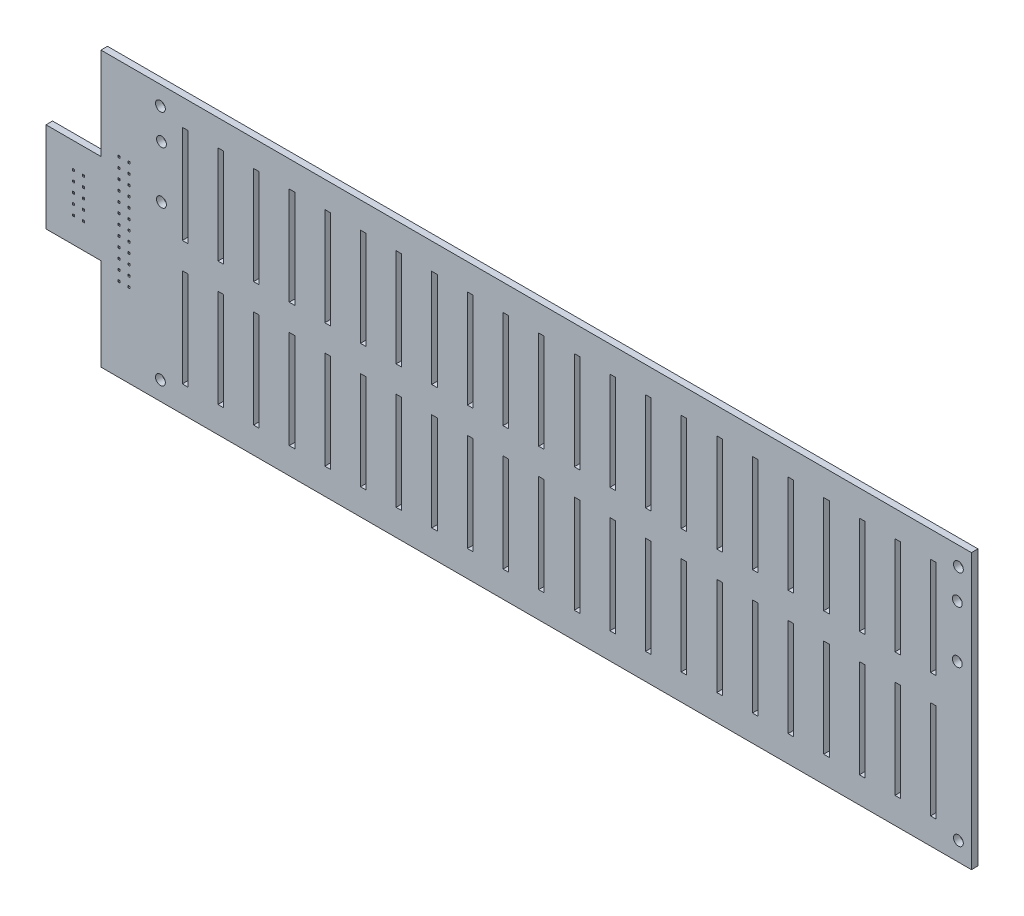
SolidWorks part; units mm, degrees
ref_plane "Front Plane" through (0, 0, 0) normal (0, 0, 1) x (1, 0, 0)
ref_plane "Top Plane" through (0, 0, 0) normal (0, 1, 0) x (1, 0, 0)
ref_plane "Right Plane" through (0, 0, 0) normal (1, 0, 0) x (0, 0, -1)
sketch "Model" plane through (0, 0, 0) normal (0, 0, 1) x (1, 0, 0)
  line L0 (-140.24, -42) -> (126.05, -42)
  line L1 (126.05, -42) -> (126.05, 42)
  line L2 (126.05, 42) -> (-140.24, 42)
  line L3 (-140.24, 42) -> (-140.24, 13.8)
  line L4 (-140.24, 13.8) -> (-157.05, 13.8)
  line L5 (-157.05, 13.8) -> (-157.05, -13.8)
  line L6 (-157.05, -13.8) -> (-140.24, -13.8)
  line L7 (-140.24, -13.8) -> (-140.24, -42)
  line L8 (-131.39, -1.18) -> (-132.03, -1.18)
  line L9 (-131.39, -1.82) -> (-131.39, -1.18)
  line L10 (-132.03, -1.82) -> (-131.39, -1.82)
  line L11 (-132.03, -1.18) -> (-132.03, -1.82)
  line L12 (-134.39, 1.82) -> (-135.03, 1.82)
  line L13 (-134.39, 1.18) -> (-134.39, 1.82)
  line L14 (-135.03, 1.18) -> (-134.39, 1.18)
  line L15 (-135.03, 1.82) -> (-135.03, 1.18)
  line L16 (-131.39, 1.82) -> (-132.03, 1.82)
  line L17 (-131.39, 1.18) -> (-131.39, 1.82)
  line L18 (-132.03, 1.18) -> (-131.39, 1.18)
  line L19 (-132.03, 1.82) -> (-132.03, 1.18)
  line L20 (-134.39, 4.82) -> (-135.03, 4.82)
  line L21 (-134.39, 4.18) -> (-134.39, 4.82)
  line L22 (-135.03, 4.18) -> (-134.39, 4.18)
  line L23 (-135.03, 4.82) -> (-135.03, 4.18)
  line L24 (-131.39, -7.18) -> (-132.03, -7.18)
  line L25 (-131.39, -7.82) -> (-131.39, -7.18)
  line L26 (-132.03, -7.82) -> (-131.39, -7.82)
  line L27 (-132.03, -7.18) -> (-132.03, -7.82)
  line L28 (-134.39, -4.18) -> (-135.03, -4.18)
  line L29 (-134.39, -4.82) -> (-134.39, -4.18)
  line L30 (-135.03, -4.82) -> (-134.39, -4.82)
  line L31 (-135.03, -4.18) -> (-135.03, -4.82)
  line L32 (-131.39, -4.18) -> (-132.03, -4.18)
  line L33 (-131.39, -4.82) -> (-131.39, -4.18)
  line L34 (-132.03, -4.82) -> (-131.39, -4.82)
  line L35 (-132.03, -4.18) -> (-132.03, -4.82)
  line L36 (-134.39, -1.18) -> (-135.03, -1.18)
  line L37 (-134.39, -1.82) -> (-134.39, -1.18)
  line L38 (-135.03, -1.82) -> (-134.39, -1.82)
  line L39 (-135.03, -1.18) -> (-135.03, -1.82)
  line L40 (-134.39, 10.82) -> (-135.03, 10.82)
  line L41 (-134.39, 10.18) -> (-134.39, 10.82)
  line L42 (-135.03, 10.18) -> (-134.39, 10.18)
  line L43 (-135.03, 10.82) -> (-135.03, 10.18)
  line L44 (-134.39, 13.82) -> (-135.03, 13.82)
  line L45 (-134.39, 13.18) -> (-134.39, 13.82)
  line L46 (-135.03, 13.18) -> (-134.39, 13.18)
  line L47 (-135.03, 13.82) -> (-135.03, 13.18)
  line L48 (-131.39, 13.82) -> (-132.03, 13.82)
  line L49 (-131.39, 13.18) -> (-131.39, 13.82)
  line L50 (-132.03, 13.18) -> (-131.39, 13.18)
  line L51 (-132.03, 13.82) -> (-132.03, 13.18)
  line L52 (-134.39, 16.82) -> (-135.03, 16.82)
  line L53 (-134.39, 16.18) -> (-134.39, 16.82)
  line L54 (-135.03, 16.18) -> (-134.39, 16.18)
  line L55 (-135.03, 16.82) -> (-135.03, 16.18)
  line L56 (-131.39, 4.82) -> (-132.03, 4.82)
  line L57 (-131.39, 4.18) -> (-131.39, 4.82)
  line L58 (-132.03, 4.18) -> (-131.39, 4.18)
  line L59 (-132.03, 4.82) -> (-132.03, 4.18)
  line L60 (-134.39, 7.82) -> (-135.03, 7.82)
  line L61 (-134.39, 7.18) -> (-134.39, 7.82)
  line L62 (-135.03, 7.18) -> (-134.39, 7.18)
  line L63 (-135.03, 7.82) -> (-135.03, 7.18)
  line L64 (-131.39, 7.82) -> (-132.03, 7.82)
  line L65 (-131.39, 7.18) -> (-131.39, 7.82)
  line L66 (-132.03, 7.18) -> (-131.39, 7.18)
  line L67 (-132.03, 7.82) -> (-132.03, 7.18)
  line L68 (-131.39, 10.82) -> (-132.03, 10.82)
  line L69 (-131.39, 10.18) -> (-131.39, 10.82)
  line L70 (-132.03, 10.18) -> (-131.39, 10.18)
  line L71 (-132.03, 10.82) -> (-132.03, 10.18)
  line L72 (-145.9, -0.32) -> (-145.26, -0.32)
  line L73 (-145.9, 0.32) -> (-145.9, -0.32)
  line L74 (-145.26, 0.32) -> (-145.9, 0.32)
  line L75 (-145.26, -0.32) -> (-145.26, 0.32)
  line L76 (-148.9, 2.68) -> (-148.26, 2.68)
  line L77 (-148.9, 3.32) -> (-148.9, 2.68)
  line L78 (-148.26, 3.32) -> (-148.9, 3.32)
  line L79 (-148.26, 2.68) -> (-148.26, 3.32)
  line L80 (-145.9, 2.68) -> (-145.26, 2.68)
  line L81 (-145.9, 3.32) -> (-145.9, 2.68)
  line L82 (-145.26, 3.32) -> (-145.9, 3.32)
  line L83 (-145.26, 2.68) -> (-145.26, 3.32)
  line L84 (-148.9, 5.68) -> (-148.26, 5.68)
  line L85 (-148.9, 6.32) -> (-148.9, 5.68)
  line L86 (-148.26, 6.32) -> (-148.9, 6.32)
  line L87 (-148.26, 5.68) -> (-148.26, 6.32)
  line L88 (-145.9, -6.32) -> (-145.26, -6.32)
  line L89 (-145.9, -5.68) -> (-145.9, -6.32)
  line L90 (-145.26, -5.68) -> (-145.9, -5.68)
  line L91 (-145.26, -6.32) -> (-145.26, -5.68)
  line L92 (-148.9, -3.32) -> (-148.26, -3.32)
  line L93 (-148.9, -2.68) -> (-148.9, -3.32)
  line L94 (-148.26, -2.68) -> (-148.9, -2.68)
  line L95 (-148.26, -3.32) -> (-148.26, -2.68)
  line L96 (-145.9, -3.32) -> (-145.26, -3.32)
  line L97 (-145.9, -2.68) -> (-145.9, -3.32)
  line L98 (-145.26, -2.68) -> (-145.9, -2.68)
  line L99 (-145.26, -3.32) -> (-145.26, -2.68)
  line L100 (-148.9, -0.32) -> (-148.26, -0.32)
  line L101 (-148.9, 0.32) -> (-148.9, -0.32)
  line L102 (-148.26, 0.32) -> (-148.9, 0.32)
  line L103 (-148.26, -0.32) -> (-148.26, 0.32)
  line L104 (-131.39, -13.18) -> (-132.03, -13.18)
  line L105 (-131.39, -13.82) -> (-131.39, -13.18)
  line L106 (-132.03, -13.82) -> (-131.39, -13.82)
  line L107 (-132.03, -13.18) -> (-132.03, -13.82)
  line L108 (-134.39, -10.18) -> (-135.03, -10.18)
  line L109 (-134.39, -10.82) -> (-134.39, -10.18)
  line L110 (-135.03, -10.82) -> (-134.39, -10.82)
  line L111 (-135.03, -10.18) -> (-135.03, -10.82)
  line L112 (-131.39, -10.18) -> (-132.03, -10.18)
  line L113 (-131.39, -10.82) -> (-131.39, -10.18)
  line L114 (-132.03, -10.82) -> (-131.39, -10.82)
  line L115 (-132.03, -10.18) -> (-132.03, -10.82)
  line L116 (-134.39, -7.18) -> (-135.03, -7.18)
  line L117 (-134.39, -7.82) -> (-134.39, -7.18)
  line L118 (-135.03, -7.82) -> (-134.39, -7.82)
  line L119 (-135.03, -7.18) -> (-135.03, -7.82)
  line L120 (-145.9, 5.68) -> (-145.26, 5.68)
  line L121 (-145.9, 6.32) -> (-145.9, 5.68)
  line L122 (-145.26, 6.32) -> (-145.9, 6.32)
  line L123 (-145.26, 5.68) -> (-145.26, 6.32)
  line L124 (-134.39, -16.18) -> (-135.03, -16.18)
  line L125 (-134.39, -16.82) -> (-134.39, -16.18)
  line L126 (-135.03, -16.82) -> (-134.39, -16.82)
  line L127 (-135.03, -16.18) -> (-135.03, -16.82)
  line L128 (-131.39, -16.18) -> (-132.03, -16.18)
  line L129 (-131.39, -16.82) -> (-131.39, -16.18)
  line L130 (-132.03, -16.82) -> (-131.39, -16.82)
  line L131 (-132.03, -16.18) -> (-132.03, -16.82)
  line L132 (-134.39, -13.18) -> (-135.03, -13.18)
  line L133 (-134.39, -13.82) -> (-134.39, -13.18)
  line L134 (-135.03, -13.82) -> (-134.39, -13.82)
  line L135 (-135.03, -13.18) -> (-135.03, -13.82)
  line L136 (-131.39, 16.82) -> (-132.03, 16.82)
  line L137 (-131.39, 16.18) -> (-131.39, 16.82)
  line L138 (-132.03, 16.18) -> (-131.39, 16.18)
  line L139 (-132.03, 16.82) -> (-132.03, 16.18)
  line L140 (-148.9, -6.32) -> (-148.26, -6.32)
  line L141 (-148.9, -5.68) -> (-148.9, -6.32)
  line L142 (-148.26, -5.68) -> (-148.9, -5.68)
  line L143 (-148.26, -6.32) -> (-148.26, -5.68)
  line L144 (-104.45, 34) -> (-104.45, 4)
  line L145 (-102.75, 34) -> (-104.45, 34)
  line L146 (-102.75, 4) -> (-102.75, 34)
  line L147 (-104.45, 4) -> (-102.75, 4)
  line L157 (-93.55, 34) -> (-93.55, 4)
  line L158 (-91.85, 34) -> (-93.55, 34)
  line L159 (-91.85, 4) -> (-91.85, 34)
  line L160 (-93.55, 4) -> (-91.85, 4)
  line L162 (-82.65, 34) -> (-82.65, 4)
  line L163 (-80.95, 34) -> (-82.65, 34)
  line L172 (-80.95, 4) -> (-80.95, 34)
  line L173 (-82.65, 4) -> (-80.95, 4)
  line L175 (-71.75, 34) -> (-71.75, 4)
  line L176 (-70.05, 34) -> (-71.75, 34)
  line L177 (-70.05, 4) -> (-70.05, 34)
  line L178 (-71.75, 4) -> (-70.05, 4)
  line L188 (-60.85, 34) -> (-60.85, 4)
  line L189 (-59.15, 34) -> (-60.85, 34)
  line L190 (-59.15, 4) -> (-59.15, 34)
  line L191 (-60.85, 4) -> (-59.15, 4)
  line L193 (-49.95, 34) -> (-49.95, 4)
  line L194 (-48.25, 34) -> (-49.95, 34)
  line L195 (-48.25, 4) -> (-48.25, 34)
  line L204 (-49.95, 4) -> (-48.25, 4)
  line L206 (-39.05, 34) -> (-39.05, 4)
  line L207 (-37.35, 34) -> (-39.05, 34)
  line L208 (-37.35, 4) -> (-37.35, 34)
  line L209 (-39.05, 4) -> (-37.35, 4)
  line L211 (-28.15, 34) -> (-28.15, 4)
  line L220 (-26.45, 34) -> (-28.15, 34)
  line L221 (-26.45, 4) -> (-26.45, 34)
  line L222 (-28.15, 4) -> (-26.45, 4)
  line L224 (-17.25, 34) -> (-17.25, 4)
  line L225 (-15.55, 34) -> (-17.25, 34)
  line L226 (-15.55, 4) -> (-15.55, 34)
  line L227 (-17.25, 4) -> (-15.55, 4)
  line L236 (-115.35, 34) -> (-115.35, 4)
  line L237 (-113.65, 34) -> (-115.35, 34)
  line L238 (-113.65, 4) -> (-113.65, 34)
  line L239 (-115.35, 4) -> (-113.65, 4)
  line L241 (-6.35, 34) -> (-6.35, 4)
  line L242 (-4.65, 34) -> (-6.35, 34)
  line L243 (-4.65, 4) -> (-4.65, 34)
  line L252 (-6.35, 4) -> (-4.65, 4)
  line L254 (4.55, 34) -> (4.55, 4)
  line L255 (6.25, 34) -> (4.55, 34)
  line L256 (6.25, 4) -> (6.25, 34)
  line L257 (4.55, 4) -> (6.25, 4)
  line L259 (15.45, 34) -> (15.45, 4)
  line L268 (17.15, 34) -> (15.45, 34)
  line L269 (17.15, 4) -> (17.15, 34)
  line L270 (15.45, 4) -> (17.15, 4)
  line L280 (26.35, 34) -> (26.35, 4)
  line L281 (28.05, 34) -> (26.35, 34)
  line L282 (28.05, 4) -> (28.05, 34)
  line L283 (26.35, 4) -> (28.05, 4)
  line L285 (37.25, 34) -> (37.25, 4)
  line L286 (38.95, 34) -> (37.25, 34)
  line L287 (38.95, 4) -> (38.95, 34)
  line L296 (37.25, 4) -> (38.95, 4)
  line L298 (48.15, 34) -> (48.15, 4)
  line L299 (49.85, 34) -> (48.15, 34)
  line L300 (49.85, 4) -> (49.85, 34)
  line L301 (48.15, 4) -> (49.85, 4)
  line L303 (59.05, 34) -> (59.05, 4)
  line L312 (60.75, 34) -> (59.05, 34)
  line L313 (60.75, 4) -> (60.75, 34)
  line L314 (59.05, 4) -> (60.75, 4)
  line L316 (69.95, 34) -> (69.95, 4)
  line L317 (71.65, 34) -> (69.95, 34)
  line L318 (71.65, 4) -> (71.65, 34)
  line L319 (69.95, 4) -> (71.65, 4)
  line L320 (0, 0) -> (0, 42) construction
  line L321 (-115.35, 19) -> (115.35, 19) construction
  line L322 (0, 0) -> (24.0524, 0) construction
  line L324 (80.85, 34) -> (80.85, 4)
  line L325 (82.55, 34) -> (80.85, 34)
  line L326 (82.55, 4) -> (82.55, 34)
  line L327 (80.85, 4) -> (82.55, 4)
  line L329 (91.75, 34) -> (91.75, 4)
  line L330 (93.45, 34) -> (91.75, 34)
  line L331 (93.45, 4) -> (93.45, 34)
  line L332 (91.75, 4) -> (93.45, 4)
  line L334 (102.65, 34) -> (102.65, 4)
  line L335 (104.35, 34) -> (102.65, 34)
  line L336 (104.35, 4) -> (104.35, 34)
  line L337 (102.65, 4) -> (104.35, 4)
  line L339 (113.55, 34) -> (113.55, 4)
  line L340 (115.25, 34) -> (113.55, 34)
  line L341 (115.25, 4) -> (115.25, 34)
  line L342 (113.55, 4) -> (115.25, 4)
  line L345 (-115.35, -19) -> (115.35, -19) construction
  line L346 (113.55, -4) -> (115.25, -4)
  line L347 (115.25, -4) -> (115.25, -34)
  line L348 (115.25, -34) -> (113.55, -34)
  line L349 (113.55, -34) -> (113.55, -4)
  line L350 (102.65, -4) -> (104.35, -4)
  line L351 (104.35, -4) -> (104.35, -34)
  line L352 (104.35, -34) -> (102.65, -34)
  line L353 (102.65, -34) -> (102.65, -4)
  line L354 (91.75, -4) -> (93.45, -4)
  line L355 (93.45, -4) -> (93.45, -34)
  line L356 (93.45, -34) -> (91.75, -34)
  line L357 (91.75, -34) -> (91.75, -4)
  line L358 (80.85, -4) -> (82.55, -4)
  line L359 (82.55, -4) -> (82.55, -34)
  line L360 (82.55, -34) -> (80.85, -34)
  line L361 (80.85, -34) -> (80.85, -4)
  line L362 (69.95, -4) -> (71.65, -4)
  line L363 (71.65, -4) -> (71.65, -34)
  line L364 (71.65, -34) -> (69.95, -34)
  line L365 (69.95, -34) -> (69.95, -4)
  line L366 (59.05, -4) -> (60.75, -4)
  line L367 (60.75, -4) -> (60.75, -34)
  line L368 (60.75, -34) -> (59.05, -34)
  line L369 (59.05, -34) -> (59.05, -4)
  line L370 (48.15, -4) -> (49.85, -4)
  line L371 (49.85, -4) -> (49.85, -34)
  line L372 (49.85, -34) -> (48.15, -34)
  line L373 (48.15, -34) -> (48.15, -4)
  line L374 (37.25, -4) -> (38.95, -4)
  line L375 (38.95, -4) -> (38.95, -34)
  line L376 (38.95, -34) -> (37.25, -34)
  line L377 (37.25, -34) -> (37.25, -4)
  line L378 (26.35, -4) -> (28.05, -4)
  line L379 (28.05, -4) -> (28.05, -34)
  line L380 (28.05, -34) -> (26.35, -34)
  line L381 (26.35, -34) -> (26.35, -4)
  line L382 (15.45, -4) -> (17.15, -4)
  line L383 (17.15, -4) -> (17.15, -34)
  line L384 (17.15, -34) -> (15.45, -34)
  line L385 (15.45, -34) -> (15.45, -4)
  line L386 (4.55, -4) -> (6.25, -4)
  line L387 (6.25, -4) -> (6.25, -34)
  line L388 (6.25, -34) -> (4.55, -34)
  line L389 (4.55, -34) -> (4.55, -4)
  line L390 (-6.35, -4) -> (-4.65, -4)
  line L391 (-4.65, -4) -> (-4.65, -34)
  line L392 (-4.65, -34) -> (-6.35, -34)
  line L393 (-6.35, -34) -> (-6.35, -4)
  line L394 (-115.35, -4) -> (-113.65, -4)
  line L395 (-113.65, -4) -> (-113.65, -34)
  line L396 (-113.65, -34) -> (-115.35, -34)
  line L397 (-115.35, -34) -> (-115.35, -4)
  line L398 (-17.25, -4) -> (-15.55, -4)
  line L399 (-15.55, -4) -> (-15.55, -34)
  line L400 (-15.55, -34) -> (-17.25, -34)
  line L401 (-17.25, -34) -> (-17.25, -4)
  line L402 (-28.15, -4) -> (-26.45, -4)
  line L403 (-26.45, -4) -> (-26.45, -34)
  line L404 (-26.45, -34) -> (-28.15, -34)
  line L405 (-28.15, -34) -> (-28.15, -4)
  line L406 (-39.05, -4) -> (-37.35, -4)
  line L407 (-37.35, -4) -> (-37.35, -34)
  line L408 (-37.35, -34) -> (-39.05, -34)
  line L409 (-39.05, -34) -> (-39.05, -4)
  line L410 (-49.95, -4) -> (-48.25, -4)
  line L411 (-48.25, -4) -> (-48.25, -34)
  line L412 (-48.25, -34) -> (-49.95, -34)
  line L413 (-49.95, -34) -> (-49.95, -4)
  line L414 (-60.85, -4) -> (-59.15, -4)
  line L415 (-59.15, -4) -> (-59.15, -34)
  line L416 (-59.15, -34) -> (-60.85, -34)
  line L417 (-60.85, -34) -> (-60.85, -4)
  line L418 (-71.75, -4) -> (-70.05, -4)
  line L419 (-70.05, -4) -> (-70.05, -34)
  line L420 (-70.05, -34) -> (-71.75, -34)
  line L421 (-71.75, -34) -> (-71.75, -4)
  line L422 (-82.65, -4) -> (-80.95, -4)
  line L423 (-80.95, -4) -> (-80.95, -34)
  line L424 (-80.95, -34) -> (-82.65, -34)
  line L425 (-82.65, -34) -> (-82.65, -4)
  line L426 (-93.55, -4) -> (-91.85, -4)
  line L427 (-91.85, -4) -> (-91.85, -34)
  line L428 (-91.85, -34) -> (-93.55, -34)
  line L429 (-93.55, -34) -> (-93.55, -4)
  line L430 (-104.45, -4) -> (-102.75, -4)
  line L431 (-102.75, -4) -> (-102.75, -34)
  line L432 (-102.75, -34) -> (-104.45, -34)
  line L433 (-104.45, -34) -> (-104.45, -4)
  line L434 (-93.55, 19) -> (137.15, 19) construction
  line L435 (-82.65, 19) -> (148.05, 19) construction
  line L436 (-71.75, 19) -> (158.95, 19) construction
  line L437 (-60.85, 19) -> (169.85, 19) construction
  line L438 (-49.95, 19) -> (180.75, 19) construction
  line L439 (-39.05, 19) -> (191.65, 19) construction
  line L440 (-28.15, 19) -> (202.55, 19) construction
  line L441 (-17.25, 19) -> (213.45, 19) construction
  line L442 (-6.35, 19) -> (224.35, 19) construction
  line L443 (4.55, 19) -> (235.25, 19) construction
  line L444 (15.45, 19) -> (246.15, 19) construction
  line L445 (26.35, 19) -> (257.05, 19) construction
  line L446 (37.25, 19) -> (267.95, 19) construction
  line L447 (48.15, 19) -> (278.85, 19) construction
  line L448 (59.05, 19) -> (289.75, 19) construction
  line L449 (69.95, 19) -> (300.65, 19) construction
  line L450 (80.85, 19) -> (311.55, 19) construction
  line L451 (91.75, 19) -> (322.45, 19) construction
  line L452 (102.65, 19) -> (333.35, 19) construction
  line L453 (113.55, 19) -> (344.25, 19) construction
  line L454 (-104.45, 19) -> (126.25, 19) construction
  circle A0 centre (-122.05, 36.25) radius 1.5
  circle A1 centre (-122.05, -36.25) radius 1.5
  circle A2 centre (122.05, -36.25) radius 1.5
  circle A3 centre (122.05, 36.25) radius 1.5
  circle A4 centre (121.73, 27) radius 1.5
  circle A5 centre (121.73, 11) radius 1.5
  circle A6 centre (-121.73, 11) radius 1.5
  circle A7 centre (-121.73, 27) radius 1.5
  dimension "D6" = 230.7
  dimension "D1" = 283.1
  dimension "D2" = 84
  dimension "D3" = 16.81
  dimension "D4" = 27.6
  dimension "D5" = 42
  dimension "D7" = 19
  dimension "D8" = 30
  dimension "D9" = 1.7
  dimension "D10" = 115.35
  dimension "D12" = 9.2
  dimension "D11" = 22
extrude "Boss-Extrude1" add sketch "Model" along normal blind 2 contours L365 L362 L363 L364
